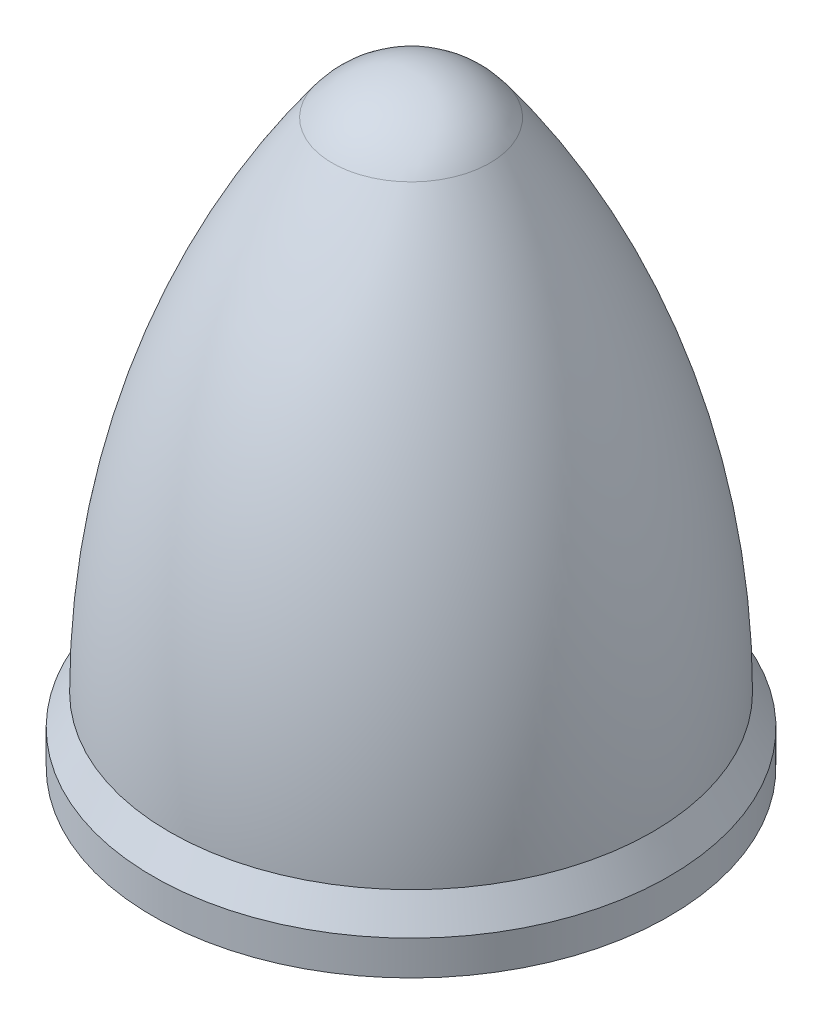
SolidWorks part; units mm, degrees
ref_plane "Front Plane" through (0, 0, 0) normal (0, 0, 1) x (1, 0, 0)
ref_plane "Top Plane" through (0, 0, 0) normal (0, 1, 0) x (1, 0, 0)
ref_plane "Right Plane" through (0, 0, 0) normal (1, 0, 0) x (0, 0, -1)
sketch "Sketch1" plane through (0, 0, 0) normal (1, 0, 0) x (0, 0, -1)
  line L0 (2.8, 0) -> (2.8, 5.5)
  line L1 (2.8, 5.5) -> (0, 5.5)
  line L2 (0, 5.5) -> (0, 15.6)
  line L3 (7, 0) -> (2.8, 0) construction
  line L4 (7, 0) -> (7.4807, -0.8769)
  line L5 (7.4807, -0.8769) -> (7.4807, -1.8769)
  line L6 (7.4807, -1.8769) -> (2.8, -1.8769)
  line L8 (2.8, -1.8769) -> (2.8, 0)
  arc A0 (0, 15.6) -> (2.2864, 14.439) centre (0, 12.7682) cw
  arc A1 (2.2864, 14.439) -> (7, 0) centre (-17.472, 0) cw
  dimension "D3" = 5.5
  dimension "D1" = 15.6
  dimension "D2" = 2.8
  dimension "D4" = 7
  dimension "D5" = 1
  dimension "D6" = 1
revolve "Revolve1" add sketch "Sketch1" angle 360 about L2
